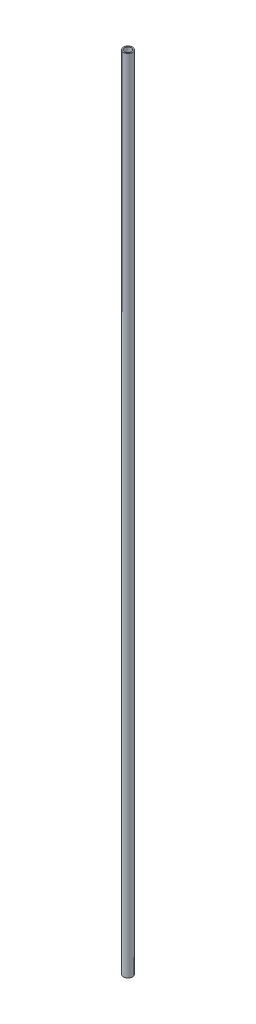
SolidWorks part; units mm, degrees
ref_plane "Front Plane" through (0, 0, 0) normal (0, 0, 1) x (1, 0, 0)
ref_plane "Top Plane" through (0, 0, 0) normal (0, 1, 0) x (1, 0, 0)
ref_plane "Right Plane" through (0, 0, 0) normal (1, 0, 0) x (0, 0, -1)
sketch "Sketch1" plane through (0, 0, 0) normal (0, 0, 1) x (1, 0, 0)
  line L0 (0, 0) -> (0, 700)
  point P6 (0, 700)
  dimension "D1" = 700
sketch "Sketch2" plane through (0, 0, 0) normal (0, 1, 0) x (1, 0, 0)
  circle A0 centre (0, 0) radius 4
  circle A1 centre (0, 0) radius 3
  dimension "D1" = 6
  dimension "D2" = 8
sweep "Sweep1" add profiles "Sketch2" path "Sketch1"
